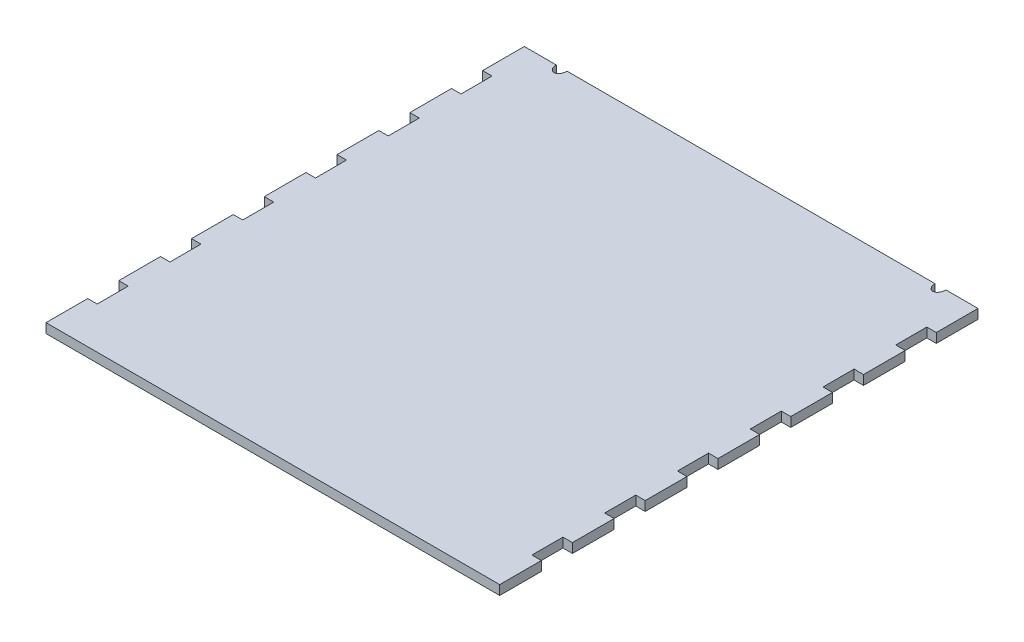
SolidWorks part; units mm, degrees
ref_plane "Front Plane" through (0, 0, 0) normal (0, 0, 1) x (1, 0, 0)
ref_plane "Top Plane" through (0, 0, 0) normal (0, 1, 0) x (1, 0, 0)
ref_plane "Right Plane" through (0, 0, 0) normal (1, 0, 0) x (0, 0, -1)
sketch "Sketch1" plane through (0, 0, 0) normal (0, 1, 0) x (1, 0, 0)
  line L0 (-146.096, 127.1637) -> (-140, 127.1637)
  line L1 (-146.096, 154.0292) -> (0, 0) construction
  line L2 (-146.096, -154.0292) -> (-146.096, -127.1637)
  line L3 (-146.096, 154.0292) -> (-125.5, 154.0292)
  line L4 (146.096, -154.0292) -> (-146.096, -154.0292)
  line L5 (-146.096, -154.0292) -> (0, 0) construction
  line L6 (0, 154.0292) -> (0, -154.0292) construction
  line L7 (-140, 127.1637) -> (-140, 107.1637)
  line L8 (-140, 107.1637) -> (-146.096, 107.1637)
  line L9 (-146.096, 80.2982) -> (-140, 80.2982)
  line L10 (-140, 80.2982) -> (-140, 60.2982)
  line L11 (-140, 60.2982) -> (-146.096, 60.2982)
  line L12 (-146.096, 33.4327) -> (-140, 33.4327)
  line L13 (-140, 33.4327) -> (-140, 13.4327)
  line L14 (-140, 13.4327) -> (-146.096, 13.4327)
  line L15 (-146.096, -13.4327) -> (-140, -13.4327)
  line L16 (-140, -13.4327) -> (-140, -33.4327)
  line L17 (-140, -33.4327) -> (-146.096, -33.4327)
  line L18 (-146.096, -60.2982) -> (-140, -60.2982)
  line L19 (-140, -60.2982) -> (-140, -80.2982)
  line L20 (-140, -80.2982) -> (-146.096, -80.2982)
  line L21 (-146.096, -107.1637) -> (-140, -107.1637)
  line L22 (-140, -107.1637) -> (-140, -127.1637)
  line L23 (-140, -127.1637) -> (-146.096, -127.1637)
  line L24 (-146.096, 127.1637) -> (-146.096, 154.0292)
  line L25 (-146.096, 80.2982) -> (-146.096, 107.1637)
  line L26 (-146.096, 33.4327) -> (-146.096, 60.2982)
  line L27 (-146.096, -13.4327) -> (-146.096, 13.4327)
  line L28 (-146.096, -60.2982) -> (-146.096, -33.4327)
  line L29 (-146.096, -107.1637) -> (-146.096, -80.2982)
  line L30 (146.096, -107.1637) -> (146.096, -80.2982)
  line L31 (146.096, -60.2982) -> (146.096, -33.4327)
  line L32 (146.096, -13.4327) -> (146.096, 13.4327)
  line L33 (146.096, 33.4327) -> (146.096, 60.2982)
  line L34 (146.096, 80.2982) -> (146.096, 107.1637)
  line L35 (146.096, 127.1637) -> (146.096, 154.0292)
  line L36 (140, -127.1637) -> (146.096, -127.1637)
  line L37 (140, -107.1637) -> (140, -127.1637)
  line L38 (146.096, -107.1637) -> (140, -107.1637)
  line L39 (140, -80.2982) -> (146.096, -80.2982)
  line L40 (140, -60.2982) -> (140, -80.2982)
  line L41 (146.096, -60.2982) -> (140, -60.2982)
  line L42 (140, -33.4327) -> (146.096, -33.4327)
  line L43 (140, -13.4327) -> (140, -33.4327)
  line L44 (146.096, -13.4327) -> (140, -13.4327)
  line L45 (140, 13.4327) -> (146.096, 13.4327)
  line L46 (140, 33.4327) -> (140, 13.4327)
  line L47 (146.096, 33.4327) -> (140, 33.4327)
  line L48 (140, 60.2982) -> (146.096, 60.2982)
  line L49 (140, 80.2982) -> (140, 60.2982)
  line L50 (146.096, 80.2982) -> (140, 80.2982)
  line L51 (140, 107.1637) -> (146.096, 107.1637)
  line L52 (140, 127.1637) -> (140, 107.1637)
  line L53 (146.096, -154.0292) -> (146.096, -127.1637)
  line L54 (-146.096, -154.0292) -> (-292.1722, 48.8544) construction
  line L55 (-292.1722, 48.8544) -> (-146.096, 154.0292) construction
  line L56 (146.096, 127.1637) -> (140, 127.1637)
  line L57 (118.5, 154.0292) -> (-118.5, 154.0292)
  line L58 (146.096, 154.0292) -> (125.5, 154.0292)
  ellipse E0 centre (-122, 154.0292) end of major axis (-122, 149.0292) minor radius 3.5 (-118.5, 154.0292) -> (-125.5, 154.0292) cw
  ellipse E1 centre (122, 154.0292) end of major axis (122, 159.0292) minor radius 3.5 (118.5, 154.0292) -> (125.5, 154.0292) ccw
  point P0 (0, 0)
  point P55 (0, 154.0292)
  point P56 (0, -154.0292)
  dimension "D1" = 180
  dimension "D2" = 6.096
  dimension "D3" = 20
  dimension "D4" = 140
  dimension "D5" = 250
  dimension "D6" = 5
  dimension "D7" = 7
  dimension "D8" = 118.5
extrude "Boss-Extrude1" add sketch "Sketch1" along normal blind 6.096
